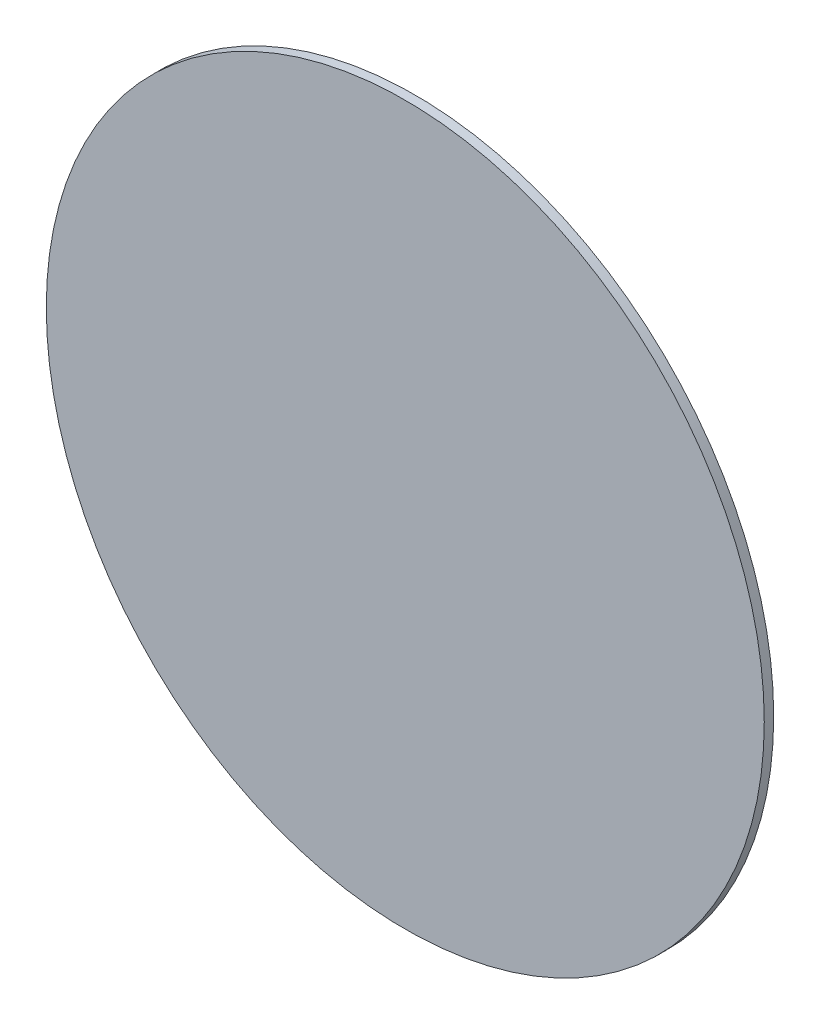
SolidWorks part; units mm, degrees
ref_plane "Plan de face" through (0, 0, 0) normal (0, 0, 1) x (1, 0, 0)
ref_plane "Plan de dessus" through (0, 0, 0) normal (0, 1, 0) x (1, 0, 0)
ref_plane "Plan de droite" through (0, 0, 0) normal (1, 0, 0) x (0, 0, -1)
sketch "Esquisse1" plane through (0, 0, 0) normal (0, 0, 1) x (1, 0, 0)
  circle A0 centre (0, 0) radius 190
extrude "Boss.-Extru.1" add sketch "Esquisse1" along normal blind 5
